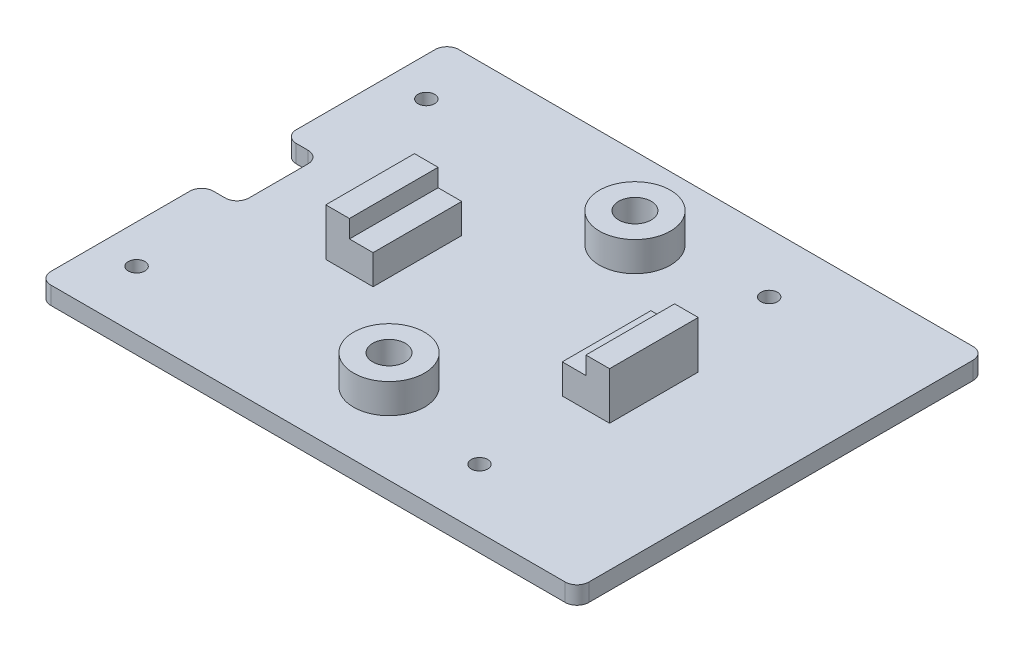
SolidWorks part; units mm, degrees
ref_plane "Front Plane" through (0, 0, 0) normal (0, 0, 1) x (1, 0, 0)
ref_plane "Top Plane" through (0, 0, 0) normal (0, 1, 0) x (1, 0, 0)
ref_plane "Right Plane" through (0, 0, 0) normal (1, 0, 0) x (0, 0, -1)
sketch "Sketch1" plane through (0, 0, 0) normal (0, 1, 0) x (1, 0, 0)
  line L1 (-45.5, 34.5) -> (45.5, 34.5)
  line L2 (-45.5, 34.5) -> (-45.5, -34.5)
  line L3 (-45.5, -34.5) -> (45.5, -34.5)
  line L4 (45.5, 34.5) -> (45.5, -34.5)
  line L5 (-45.5, 34.5) -> (45.5, -34.5) construction
  line L6 (-45.5, -34.5) -> (45.5, 34.5) construction
  point P0 (0, 0)
  dimension "D1" = 91
  dimension "D2" = 69
extrude "Boss-Extrude1" add sketch "Sketch1" along normal blind 3
sketch "Sketch2" plane through (0, 3, 0) normal (0, 1, 0) x (1, 0, 0)
  line L0 (-45.5, 34.5) -> (-45.5, -34.5) construction
  line L1 (-45.5, 7) -> (-39.5, 7)
  line L2 (-45.5, 7) -> (-45.5, -7)
  line L3 (-45.5, -7) -> (-39.5, -7)
  line L4 (-39.5, 7) -> (-39.5, -7)
  point P6 (-39.5, 0)
  dimension "D1" = 14
  dimension "D2" = 6
extrude "Cut-Extrude1" cut sketch "Sketch2" against normal through all
sketch "Sketch3" plane through (0, 3, 0) normal (0, 1, 0) x (1, 0, 0)
  line L0 (-45.5, 34.5) -> (-45.5, 7) construction
  line L1 (45.5, 34.5) -> (-45.5, 34.5) construction
  line L2 (-1.65, 0) -> (1.65, 0) construction
  circle A0 centre (-39, 24.5) radius 1.4
  circle A1 centre (19, 24.5) radius 1.4
  circle A2 centre (19, -24.5) radius 1.4
  circle A3 centre (-39, -24.5) radius 1.4
  dimension "D2" = 10
  dimension "D3" = 2.8
  dimension "D5" = 2.8
  dimension "D1" = 6.5
  dimension "D4" = 64.5
extrude "Cut-Extrude2" cut sketch "Sketch3" against normal through all
fillet "Fillet1" radius 2 8 edges at (45.5, 1.5, -34.5) (45.5, 1.5, 34.5) (-45.5, 1.5, 34.5) (-45.5, 1.5, 7) (-39.5, 1.5, 7) (-39.5, 1.5, -7) (-45.5, 1.5, -7) (-45.5, 1.5, -34.5)
sketch "Sketch5" plane through (0, 0, 0) normal (0, -1, 0) x (-1, 0, 0)
  line L0 (0, -20.8) -> (0, 20.8) construction
  circle A0 centre (0, -20.8) radius 2.75
  circle A1 centre (0, 20.8) radius 2.75
  point P6 (0, -20.8)
  point P8 (0, 0)
  dimension "D2" = 5.5
  dimension "D3" = 5.5
  dimension "D1" = 41.6
sketch "Sketch6" plane through (0, 3, 0) normal (0, 1, 0) x (1, 0, 0)
  line L0 (20, 0) -> (-20, 0) construction
  line L1 (-24, 7.5) -> (-16, 7.5)
  line L2 (-24, 7.5) -> (-24, -7.5)
  line L3 (-24, -7.5) -> (-16, -7.5)
  line L4 (-16, 7.5) -> (-16, -7.5)
  line L5 (-24, 7.5) -> (-16, -7.5) construction
  line L6 (-24, -7.5) -> (-16, 7.5) construction
  line L7 (16, 7.5) -> (24, 7.5)
  line L8 (16, 7.5) -> (16, -7.5)
  line L9 (16, -7.5) -> (24, -7.5)
  line L10 (24, 7.5) -> (24, -7.5)
  line L11 (16, 7.5) -> (24, -7.5) construction
  line L12 (16, -7.5) -> (24, 7.5) construction
  circle A1 centre (0, -20.8) radius 6
  circle A3 centre (0, 20.8) radius 6
  point P1 (-20, 0)
  point P11 (20, 0)
  point P20 (0, 0)
  dimension "D1" = 12
  dimension "D2" = 12
  dimension "D3" = 40
  dimension "D4" = 8
  dimension "D5" = 8
  dimension "D6" = 15
  dimension "D7" = 15
extrude "Boss-Extrude2" add sketch "Sketch6" along normal blind 5
extrude "Cut-Extrude3" cut sketch "Sketch5" against normal through all
sketch "Sketch7" plane through (0, 8, 0) normal (0, 1, 0) x (1, 0, 0)
  line L5 (24, 7.5) -> (16, 7.5) construction
  line L6 (20, 7.5) -> (24, 7.5)
  line L7 (20, 7.5) -> (20, -7.5)
  line L8 (20, -7.5) -> (24, -7.5)
  line L9 (24, 7.5) -> (24, -7.5)
  line L10 (16, -7.5) -> (24, -7.5) construction
  line L11 (16, -7.5) -> (24, -7.5) construction
  line L12 (-24, -7.5) -> (-16, -7.5) construction
  line L13 (-24, 7.5) -> (-20, 7.5)
  line L14 (-24, 7.5) -> (-24, -7.5)
  line L15 (-24, -7.5) -> (-20, -7.5)
  line L16 (-20, 7.5) -> (-20, -7.5)
  line L17 (24, -7.5) -> (24, 7.5) construction
extrude "Boss-Extrude3" add sketch "Sketch7" along normal blind 3
